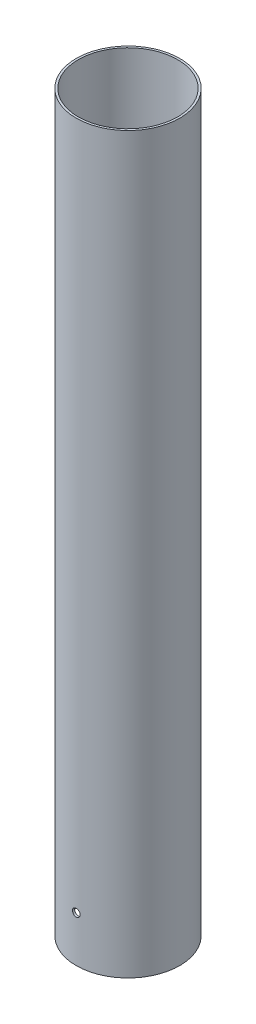
SolidWorks part; units mm, degrees
material "Cardboard Tube"
ref_plane "Front Plane" through (0, 0, 0) normal (0, 0, 1) x (1, 0, 0)
ref_plane "Top Plane" through (0, 0, 0) normal (0, 1, 0) x (1, 0, 0)
ref_plane "Right Plane" through (0, 0, 0) normal (1, 0, 0) x (0, 0, -1)
sketch "Sketch1" plane through (0, 0, 0) normal (0, 1, 0) x (1, 0, 0)
  circle A0 centre (0, 0) radius 41.25
  circle A1 centre (0, 0) radius 43
  dimension "D1" = 1.75
  dimension "D2" = 86
extrude "Boss-Extrude1" add sketch "Sketch1" along normal blind 609.6
sketch "Sketch2" plane through (0, 0, 0) normal (0, 0, 1) x (1, 0, 0)
  line L0 (-43, 0) -> (43, 0) construction
  circle A0 centre (0, 38.1) radius 3.175
  dimension "D1" = 38.1
  dimension "D2" = 6.35
extrude "Cut-Extrude1" cut sketch "Sketch2" against normal through all both and the other way through all
